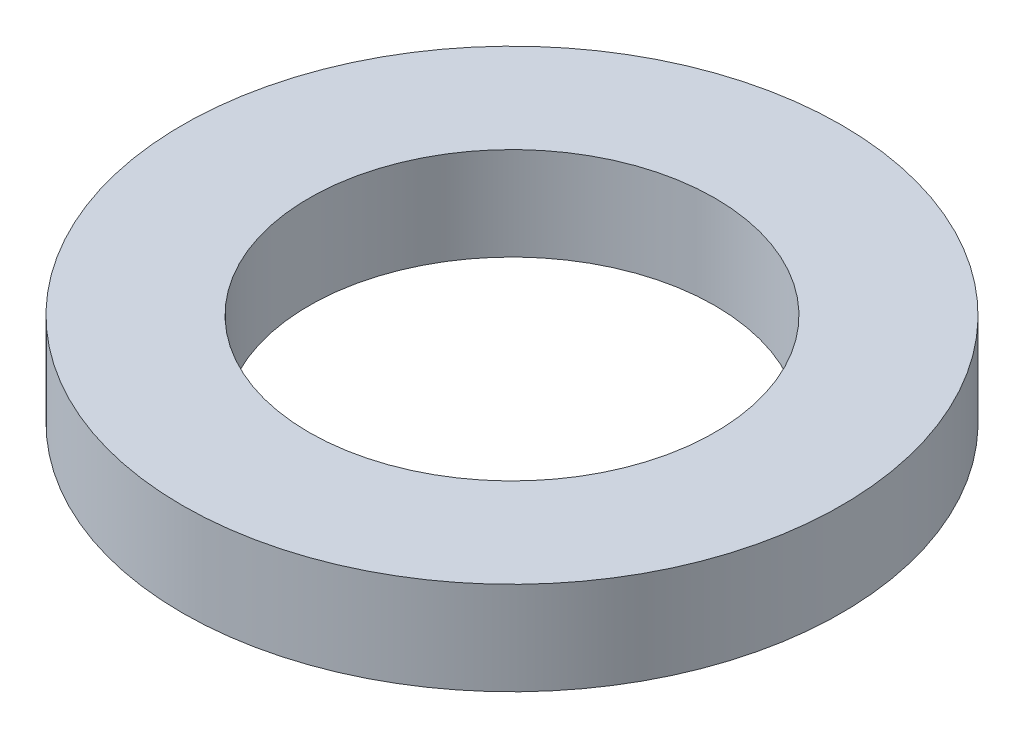
SolidWorks part; units mm, degrees
material "Cast Alloy Steel"
ref_plane "Front Plane" through (0, 0, 0) normal (0, 0, 1) x (1, 0, 0)
ref_plane "Top Plane" through (0, 0, 0) normal (0, 1, 0) x (1, 0, 0)
ref_plane "Right Plane" through (0, 0, 0) normal (1, 0, 0) x (0, 0, -1)
sketch "Sketch2" plane through (0, 0, 0) normal (0, 1, 0) x (1, 0, 0)
  circle A0 centre (0, 0) radius 885
  dimension "D1" = 1770
extrude "Boss-Extrude1" add sketch "Sketch2" along normal blind 250 contours A0
sketch "Sketch3" plane through (0, 250, 0) normal (0, 1, 0) x (1, 0, 0)
  circle A0 centre (0, 0) radius 545
  dimension "D1" = 1090
extrude "Cut-Extrude1" cut sketch "Sketch3" against normal blind 250
